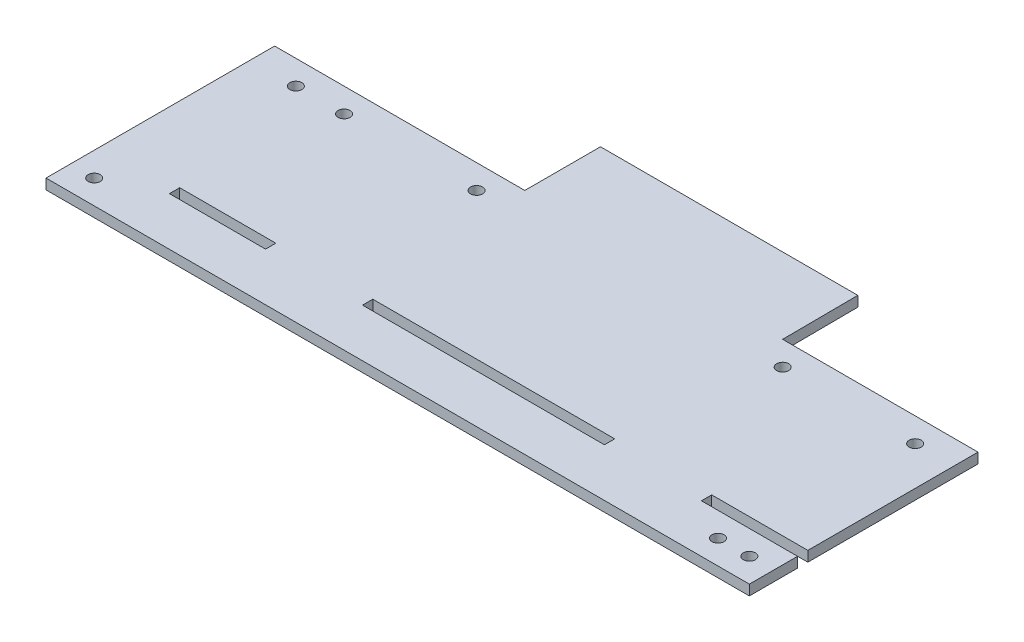
SolidWorks part; units mm, degrees
ref_plane "Front Plane" through (0, 0, 0) normal (0, 0, 1) x (1, 0, 0)
ref_plane "Top Plane" through (0, 0, 0) normal (0, 1, 0) x (1, 0, 0)
ref_plane "Right Plane" through (0, 0, 0) normal (1, 0, 0) x (0, 0, -1)
sketch "Sketch1" plane through (0, 0, 0) normal (0, 1, 0) x (1, 0, 0)
  line L0 (-91.8337, -47.6885) -> (-86.7283, -47.6885) construction
  line L1 (-165.481, -47.5361) -> (165.481, -47.5361)
  line L2 (-165.481, -47.5361) -> (-165.481, 47.5361)
  line L3 (-165.481, 47.5361) -> (165.481, 47.5361)
  line L4 (165.481, -47.5361) -> (165.481, 47.5361)
  line L5 (-165.481, -47.5361) -> (165.481, 47.5361) construction
  line L6 (-165.481, 47.5361) -> (165.481, -47.5361) construction
  line L7 (-165.481, -47.5361) -> (-114.8334, -47.5361)
  line L8 (-165.481, -47.5361) -> (-165.481, -42.1259)
  line L9 (-165.481, -42.1259) -> (-114.8334, -42.1259)
  line L10 (-114.8334, -47.5361) -> (-114.8334, -42.1259)
  line L11 (-63.7286, -47.5361) -> (63.7286, -47.5361)
  line L12 (-63.7286, -47.5361) -> (-63.7286, -42.1259)
  line L13 (-63.7286, -42.1259) -> (63.7286, -42.1259)
  line L14 (63.7286, -47.5361) -> (63.7286, -42.1259)
  line L15 (165.481, -47.5361) -> (114.8334, -47.5361)
  line L16 (165.481, -47.5361) -> (165.481, -42.1259)
  line L17 (165.481, -42.1259) -> (114.8334, -42.1259)
  line L18 (114.8334, -47.5361) -> (114.8334, -42.1259)
  line L19 (-165.481, 47.5361) -> (-205.105, 47.5361)
  line L20 (-165.481, 47.5361) -> (-165.481, -47.5361)
  line L21 (-165.481, -47.5361) -> (-205.105, -47.5361)
  line L22 (-205.105, 47.5361) -> (-205.105, -47.5361)
  line L23 (-205.105, -47.5361) -> (165.481, -47.5361)
  line L24 (-205.105, -47.5361) -> (-205.105, -72.9361)
  line L25 (-205.105, -72.9361) -> (165.481, -72.9361)
  line L26 (165.481, -47.5361) -> (165.481, -72.9361)
  line L27 (-91.9861, -47.5361) -> (-86.5759, -47.5361)
  line L28 (-91.9861, -47.5361) -> (-91.9861, -60.2361)
  line L29 (-91.9861, -60.2361) -> (-86.5759, -60.2361)
  line L30 (-86.5759, -47.5361) -> (-86.5759, -60.2361)
  line L31 (-86.7283, -47.6885) -> (-86.7283, -60.0837) construction
  line L32 (-91.8337, -60.0837) -> (-86.7283, -60.0837) construction
  line L33 (-91.8337, -47.6885) -> (-91.8337, -60.0837) construction
  line L34 (86.7283, -47.6885) -> (91.8337, -47.6885) construction
  line L35 (86.5759, -47.5361) -> (91.9861, -47.5361)
  line L36 (86.5759, -47.5361) -> (86.5759, -60.2361)
  line L37 (86.5759, -60.2361) -> (91.9861, -60.2361)
  line L38 (91.9861, -47.5361) -> (91.9861, -60.2361)
  line L39 (91.8337, -47.6885) -> (91.8337, -60.0837) construction
  line L40 (86.7283, -60.0837) -> (91.8337, -60.0837) construction
  line L41 (86.7283, -47.6885) -> (86.7283, -60.0837) construction
  line L42 (-73.3069, 47.5361) -> (-73.3069, -42.1259)
  line L43 (-73.3069, -42.1259) -> (62.5475, -42.1259)
  line L44 (62.5475, -42.1259) -> (62.5475, 47.5361)
  circle A0 centre (-155.829, 34.8361) radius 3.175
  circle A1 centre (-86.0069, 34.8361) radius 3.175
  circle A2 centre (75.2475, 34.8361) radius 3.175
  circle A3 centre (145.0696, 34.8361) radius 3.175
  circle A4 centre (-181.229, 34.8361) radius 3.175
  circle A5 centre (-192.405, -60.2361) radius 3.175
  circle A6 centre (152.781, -60.2361) radius 3.175
  circle A9 centre (136.271, -60.2361) radius 3.175
  point P0 (0, 0)
  dimension "D10" = 69.8221
  dimension "D18" = 39.624
  dimension "D22" = 6.35
  dimension "D23" = 12.7
  dimension "D25" = 12.7
  dimension "D27" = 12.7
  dimension "D28" = 12.7
  dimension "D39" = 29.21
  dimension "D1" = 330.962
  dimension "D2" = 95.0722
  dimension "D3" = 50.6476
  dimension "D4" = 5.4102
  dimension "D5" = 50.6476
  dimension "D6" = 5.4102
  dimension "D7" = 51.1048
  dimension "D8" = 51.1048
  dimension "D9" = 5.4102
  dimension "D11" = 9.652
  dimension "D12" = 240.7285
  dimension "D13" = 69.8221
  dimension "D14" = 12.7
  dimension "D15" = 12.7
  dimension "D16" = 12.7
  dimension "D17" = 12.7
  dimension "D19" = 25.4
  dimension "D20" = 12.7
  dimension "D21" = 25.4
  dimension "D24" = 12.7
  dimension "D26" = 12.7
  dimension "D30" = 5.4102
  dimension "D31" = 12.7
  dimension "D32" = 22.8473
  dimension "D33" = 22.8473
  dimension "D35" = 12.7
  dimension "D36" = 5.4102
  dimension "D37" = 22.8473
  dimension "D34" = 0.1524
  dimension "D38" = 0.1524
extrude "Boss-Extrude1" add sketch "Sketch1" along normal blind 5.4102 contours L43 L42 L3 L2 L9 L10 L1 L23 L12 A1 A0 | L1 L38 L37 L36 L30 L29 L28 L21 L24 L25 L26 A9 A6 A5 | L38 L23 L36 L37 | L44 L13 L14 L1 L23 L18 L17 L4 L3 A3 A2 | L19 L22 L21 L2 A4
sketch "Sketch2" plane through (0, 5.4102, 0) normal (0, 1, 0) x (1, 0, 0)
  line L0 (-73.3069, 47.5361) -> (-73.3069, 87.4141)
  line L1 (-73.3069, 87.4141) -> (62.2805, 87.4141)
  line L2 (62.2805, 87.4141) -> (62.5475, 47.5361)
  line L3 (62.5475, 47.5361) -> (165.481, 47.5361) construction
  line L4 (62.5475, 47.5361) -> (62.5475, -42.1259)
  line L5 (62.5475, -42.1259) -> (63.7286, -42.1259)
  line L6 (63.7286, -42.1259) -> (63.7286, -47.5361)
  line L7 (63.7286, -47.5361) -> (-63.7286, -47.5361)
  line L8 (-63.7286, -47.5361) -> (-63.7286, -42.1259)
  line L9 (-63.7286, -42.1259) -> (-73.3069, -42.1259)
  line L10 (-73.3069, -42.1259) -> (-73.3069, 47.5361)
  line L11 (-63.7286, -42.1259) -> (62.5475, -42.1259)
  line M8 (62.5475, 47.5361) -> (62.5475, -42.1259)
  line M13 (-63.7286, -42.1259) -> (-73.3069, -42.1259)
  line M14 (-73.3069, -42.1259) -> (-73.3069, 47.5361)
  dimension "D1" = 129.54
extrude "Boss-Extrude3" add sketch "Sketch2" against normal blind 5.4102 contours L11 L2 L1 L0 M13 M8 M14
